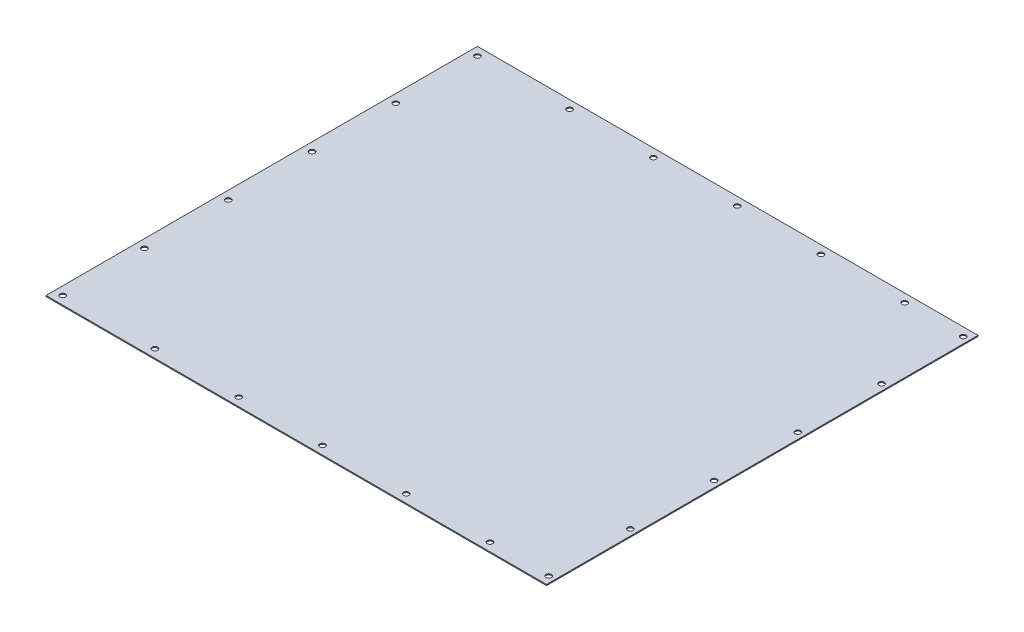
SolidWorks part; units mm, degrees
material "6061-T6 (SS)"
ref_plane "Front" through (0, 0, 0) normal (0, 0, 1) x (1, 0, 0)
ref_plane "Top" through (0, 0, 0) normal (0, 1, 0) x (1, 0, 0)
ref_plane "Right" through (0, 0, 0) normal (1, 0, 0) x (0, 0, -1)
sketch "Sketch1" plane through (0, 0, 0) normal (0, 1, 0) x (1, 0, 0)
  line L1 (0, 0) -> (758.825, 0)
  line L2 (0, 0) -> (0, 654.05)
  line L3 (0, 654.05) -> (758.825, 654.05)
  line L4 (758.825, 0) -> (758.825, 654.05)
  dimension "D1" = 758.825
  dimension "D2" = 654.05
extrude "Boss-Extrude1" add sketch "Sketch1" along normal blind 1.5875
hole_wizard "21/64 (0.32813) Diameter Hole1" positions "Sketch2" profile "Sketch3" hole size "21/64" standard "ANSI Inch" end condition through all
sketch "Sketch2" plane through (0, 1.5875, 0) normal (0, 1, 0) x (1, 0, 0)
  line L0 (0, 654.05) -> (0, 0) construction
  line L1 (0, 0) -> (758.825, 0) construction
  point P0 (12.7, 12.7)
  dimension "D1" = 12.7
  dimension "D2" = 12.7
sketch "Sketch3" plane through (12.7, 1.5875, -12.7) normal (1, 0, 0) x (0, 0, 1)
  line L0 (0, 0) -> (0, 1.5875)
  line L1 (0, 1.5875) -> (4.1673, 1.5875)
  line L2 (4.1673, 1.5875) -> (4.1673, 0)
  line L5 (4.1673, 0) -> (0, 0)
  line L11 (0, -6.35) -> (0, 107.95) construction
  dimension "Thru Hole Dia." = 8.3345
  dimension "Thru Hole Depth" = 1.5875
pattern_linear "LPattern1" count 2 spacing 736.6 along (1, 0, 0) count 2 spacing 628.65 along (0, 0, -1) of "21/64 (0.32813) Diameter Hole1"
hole_wizard "21/64 (0.32813) Diameter Hole2" positions "Sketch4" profile "Sketch5" hole size "21/64" standard "ANSI Inch" end condition through all
sketch "Sketch4" plane through (0, 1.5875, 0) normal (0, 1, 0) x (1, 0, 0)
  line L0 (0, 0) -> (758.825, 0) construction
  line L1 (0, 654.05) -> (0, 0) construction
  point P0 (152.4, 12.7)
  dimension "D1" = 12.7
  dimension "D2" = 152.4
sketch "Sketch5" plane through (152.4, 1.5875, -12.7) normal (1, 0, 0) x (0, 0, 1)
  line L0 (0, 0) -> (0, 1.5875)
  line L1 (0, 1.5875) -> (4.1673, 1.5875)
  line L2 (4.1673, 1.5875) -> (4.1673, 0)
  line L5 (4.1673, 0) -> (0, 0)
  line L11 (0, -6.35) -> (0, 107.95) construction
  dimension "Thru Hole Dia." = 8.3345
  dimension "Thru Hole Depth" = 1.5875
pattern_linear "LPattern2" count 5 spacing 127 along (1, 0, 0) count 2 spacing 628.65 along (0, 0, -1) of "21/64 (0.32813) Diameter Hole2"
hole_wizard "21/64 (0.32813) Diameter Hole3" positions "Sketch6" profile "Sketch7" hole size "21/64" standard "ANSI Inch" end condition through all
sketch "Sketch6" plane through (0, 1.5875, 0) normal (0, 1, 0) x (1, 0, 0)
  line L0 (0, 654.05) -> (0, 0) construction
  line L1 (0, 0) -> (758.825, 0) construction
  point P0 (12.7, 136.525)
  dimension "D1" = 12.7
  dimension "D2" = 136.525
sketch "Sketch7" plane through (12.7, 1.5875, -136.525) normal (1, 0, 0) x (0, 0, 1)
  line L0 (0, 0) -> (0, 1.5875)
  line L1 (0, 1.5875) -> (4.1673, 1.5875)
  line L2 (4.1673, 1.5875) -> (4.1673, 0)
  line L5 (4.1673, 0) -> (0, 0)
  line L11 (0, -6.35) -> (0, 107.95) construction
  dimension "Thru Hole Dia." = 8.3345
  dimension "Thru Hole Depth" = 1.5875
pattern_linear "LPattern6" count 4 spacing 127 along (0, 0, -1) count 2 spacing 736.6 along (1, 0, 0) of "21/64 (0.32813) Diameter Hole3"
